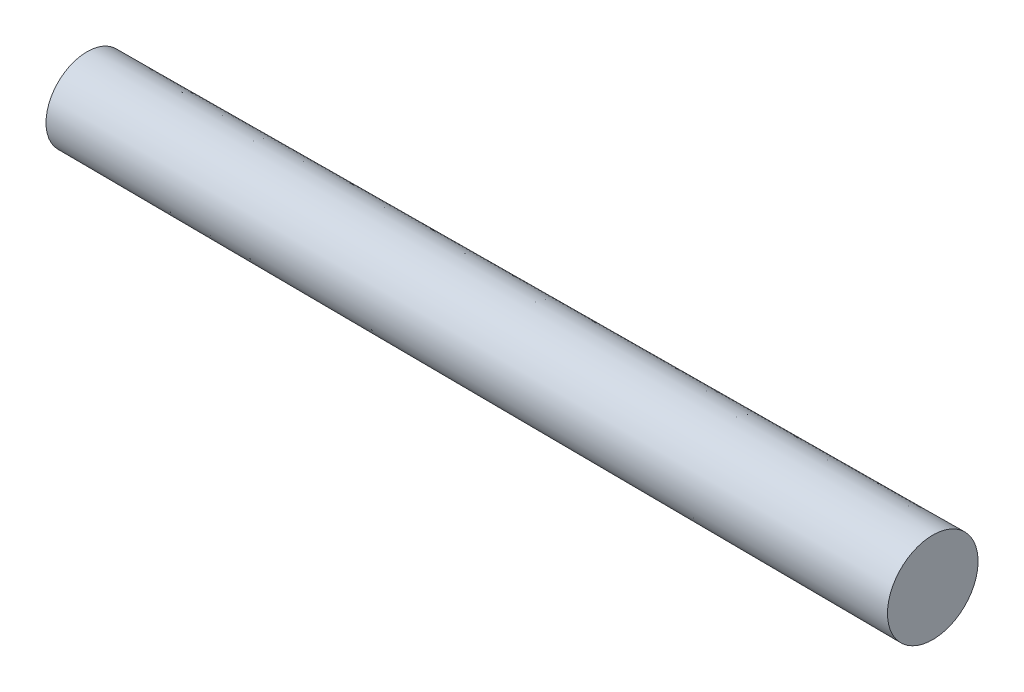
SolidWorks part; units mm, degrees
ref_plane "Front Plane" through (0, 0, 0) normal (0, 0, 1) x (1, 0, 0)
ref_plane "Top Plane" through (0, 0, 0) normal (0, 1, 0) x (1, 0, 0)
ref_plane "Right Plane" through (0, 0, 0) normal (1, 0, 0) x (0, 0, -1)
sketch "Sketch1" plane through (0, 0, 0) normal (0, 0, 1) x (1, 0, 0)
  line L0 (0, 0) -> (56, 0)
  line L1 (56, 0) -> (56, 3)
  line L2 (0, 0) -> (0, 2.72)
  line L3 (0, 2.72) -> (56, 3)
revolve "Revolve1" add sketch "Sketch1" angle 360 about L0
